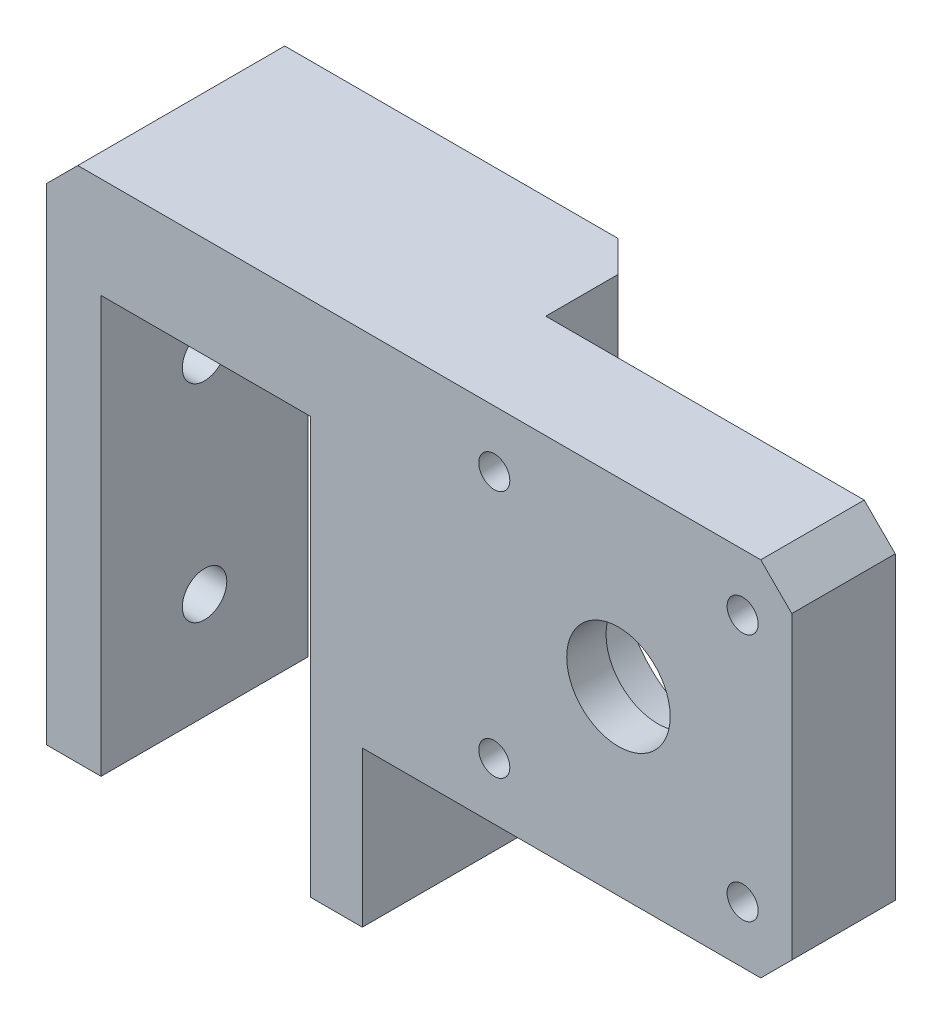
SolidWorks part; units mm, degrees
ref_plane "前视基准面" through (0, 0, 0) normal (0, 0, 1) x (1, 0, 0)
ref_plane "上视基准面" through (0, 0, 0) normal (0, 1, 0) x (1, 0, 0)
ref_plane "右视基准面" through (0, 0, 0) normal (1, 0, 0) x (0, 0, -1)
sketch "草图5" plane through (0, 0, 0) normal (0, 0, 1) x (1, 0, 0)
  line L0 (0, 0) -> (0, 50)
  line L1 (0, 50) -> (72, 50)
  line L2 (72, 50) -> (72, 15)
  line L3 (72, 15) -> (30.5, 15)
  line L4 (30.5, 15) -> (30.5, 0)
  line L5 (30.5, 0) -> (25.5, 0)
  line L6 (5, 0) -> (5, 40.5)
  line L7 (5, 40.5) -> (25.5, 40.5)
  line L8 (25.5, 40.5) -> (25.5, 0)
  line L9 (5, 0) -> (0, 0)
  circle A0 centre (55.25, 32.5) radius 5
  circle A1 centre (43.25, 44.5) radius 1.5
  circle A2 centre (67.25, 44.5) radius 1.5
  circle A3 centre (43.25, 20.5) radius 1.5
  circle A4 centre (67.25, 20.5) radius 1.5
  dimension "D10" = 10
  dimension "D15" = 3
  dimension "D1" = 50
  dimension "D2" = 40.5
  dimension "D3" = 20.5
  dimension "D4" = 5
  dimension "D5" = 5
  dimension "D6" = 72
  dimension "D7" = 35
  dimension "D8" = 16.75
  dimension "D9" = 17.5
  dimension "D11" = 12
  dimension "D12" = 12
  dimension "D13" = 12
  dimension "D14" = 12
extrude "凸台-拉伸1" add sketch "草图5" along normal blind 20
sketch "草图6" plane through (0, 0, 0) normal (-1, 0, 0) x (0, 0, 1)
  line L1 (20, 0) -> (0, 0) construction
  line L2 (20, 50) -> (20, 0) construction
  circle A0 centre (10, 10.25) radius 2.15
  circle A1 centre (10, 30.25) radius 2.15
  dimension "D4" = 4.3
  dimension "D1" = 20
  dimension "D2" = 10.25
  dimension "D3" = 10
extrude "切除-拉伸3" cut sketch "草图6" against normal blind 20
sketch "草图7" plane through (30.5, 0, 0) normal (1, 0, 0) x (0, 0, -1)
  circle A0 centre (-10, 10.25) radius 2.15 construction
  circle A1 centre (-10, 10.25) radius 2.15
extrude "切除-拉伸4" cut sketch "草图7" against normal blind 20
sketch "草图8" plane through (0, 0, 0) normal (0, 0, -1) x (-1, 0, 0)
  line L0 (-30.5, 15) -> (-72, 15) construction
  line L1 (-72, 50) -> (-38.2227, 50)
  line L2 (-72, 50) -> (-72, 15)
  line L3 (-72, 15) -> (-38.2227, 15)
  line L4 (-38.2227, 50) -> (-38.2227, 15)
extrude "切除-拉伸5" cut sketch "草图8" against normal blind 10
sketch "草图9" plane through (0, 0, 10) normal (0, 0, -1) x (-1, 0, 0)
  circle A0 centre (-55.25, 32.5) radius 9.75
  dimension "D1" = 19.5
extrude "切除-拉伸6" cut sketch "草图9" against normal blind 6.2
chamfer "倒角1" distance 3 angle 45 4 edges at (0, 50, 10) (38.2227, 32.5, 0) (72, 15, 15) (72, 50, 15)
sketch "草图10" plane through (5, 0, 0) normal (1, 0, 0) x (0, 0, -1)
  line L4 (0, 0) -> (0, 40.5)
  line L5 (0, 40.5) -> (-20, 40.5)
  line L6 (-20, 40.5) -> (-20, 0)
  line L7 (-20, 0) -> (0, 0)
  line L8 (0, 0) -> (0, 40.5)
  line L9 (0, 40.5) -> (-20, 40.5)
  line L10 (-20, 40.5) -> (-20, 0)
  line L11 (-20, 0) -> (0, 0)
  circle A0 centre (-10, 10.25) radius 2.15 construction
  circle A1 centre (-10, 30.25) radius 2.15 construction
  circle A2 centre (-10, 10.25) radius 2.15
  circle A3 centre (-10, 30.25) radius 2.15
  dimension "D1" = 0
extrude "凸台-拉伸2" add sketch "草图10" along normal blind 0.25
sketch "草图11" plane through (0, 40.5, 0) normal (0, -1, 0) x (1, 0, 0)
  line L4 (25.5, 20) -> (5.25, 20)
  line L5 (5.25, 20) -> (5.25, 0)
  line L6 (5.25, 0) -> (25.5, 0)
  line L7 (25.5, 0) -> (25.5, 20)
  line L8 (25.5, 20) -> (5.25, 20)
  line L9 (5.25, 20) -> (5.25, 0)
  line L10 (5.25, 0) -> (25.5, 0)
  line L11 (25.5, 0) -> (25.5, 20)
  dimension "D1" = 0
extrude "凸台-拉伸3" add sketch "草图11" along normal blind 0.25
